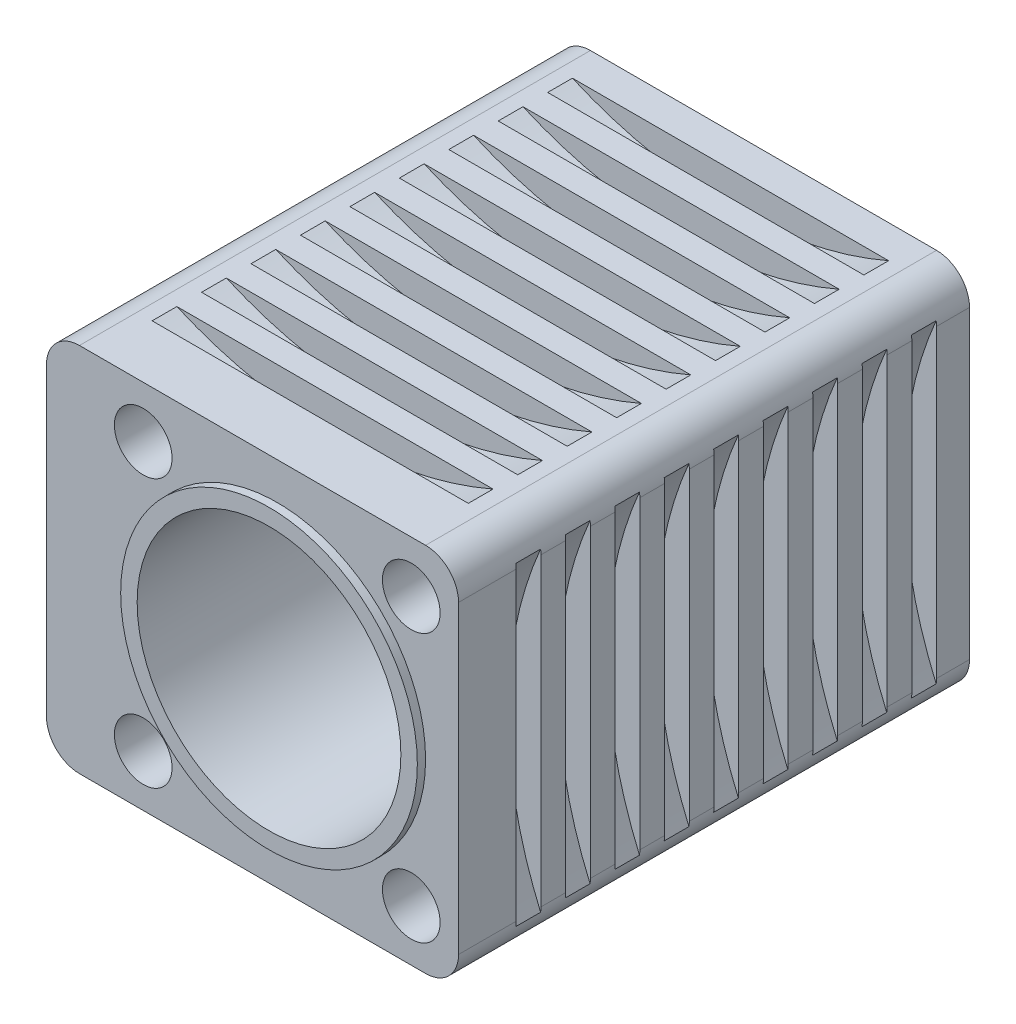
SolidWorks part; units mm, degrees
ref_plane "Front Plane" through (0, 0, 0) normal (0, 0, 1) x (1, 0, 0)
ref_plane "Top Plane" through (0, 0, 0) normal (0, 1, 0) x (1, 0, 0)
ref_plane "Right Plane" through (0, 0, 0) normal (1, 0, 0) x (0, 0, -1)
sketch "Sketch1" plane through (0, 0, 0) normal (0, 0, 1) x (1, 0, 0)
  line L1 (18, 22.5) -> (-24, 22.5)
  line L2 (22, 18.5) -> (22, -18.5)
  line L3 (18, -22.5) -> (-24, -22.5)
  line L4 (-28, 18.5) -> (-28, -18.5)
  arc A0 (22, -18.5) -> (18, -22.5) centre (18, -18.5) cw
  arc A1 (-24, -22.5) -> (-28, -18.5) centre (-24, -18.5) cw
  arc A2 (-24, 22.5) -> (-28, 18.5) centre (-24, 18.5) ccw
  arc A3 (18, 22.5) -> (22, 18.5) centre (18, 18.5) cw
  point P7 (22, -22.5)
  point P12 (-28, 22.5)
  point P15 (22, 22.5)
  dimension "D5" = 4
  dimension "D1" = 50
  dimension "D2" = 45
  dimension "D3" = 22
  dimension "D4" = 22.5
extrude "Boss-Extrude1" add sketch "Sketch1" along normal mid plane 62
sketch "Sketch2" plane through (0, 0, 31) normal (0, 0, 1) x (1, 0, 0)
  circle A0 centre (0, 0) radius 18
  dimension "D1" = 36
extrude "Boss-Extrude2" add sketch "Sketch2" along normal mid plane 2
sketch "Sketch3" plane through (0, 0, 32) normal (0, 0, 1) x (1, 0, 0)
  circle A0 centre (0, 0) radius 16
  dimension "D1" = 32
extrude "Cut-Extrude1" cut sketch "Sketch3" against normal through all
sketch "Sketch4" plane through (0, 0, -31) normal (0, 0, -1) x (-1, 0, 0)
  line L5 (28, 18.5) -> (28, -18.5) construction
  line L6 (12.8724, 2) -> (12.8724, -2)
  line L7 (23.4909, 2) -> (12.8724, 2)
  line L8 (22.61, -2) -> (12.8724, -2)
  arc A2 (23.4909, 2) -> (22.61, -2) centre (22.61, 0.097) cw
  dimension "D1" = 5.39
extrude "Cut-Extrude2" cut sketch "Sketch4" against normal blind 2
sketch "Sketch5" plane through (0, 0, -31) normal (0, 0, -1) x (-1, 0, 0)
  line L0 (0, 0) -> (-23, 0) construction
  line L1 (0, 0) -> (-16.2635, 16.2635) construction
  circle A0 centre (0, 0) radius 23 construction
  circle A1 centre (-16.2635, 16.2635) radius 3.5
  circle A2 centre (16.2635, 16.2635) radius 3.5
  circle A3 centre (16.2635, -16.2635) radius 3.5
  circle A4 centre (-16.2635, -16.2635) radius 3.5
  point P15 (0, 0)
  dimension "D1" = 46
  dimension "D3" = 7
  dimension "D2" = 45
  dimension "D4" = 4
extrude "Cut-Extrude3" cut sketch "Sketch5" against normal through all
ref_plane "Plane1" through (-3, 0, 0) normal (1, 0, 0) x (0, 0, -1)
sketch "Sketch6" plane through (-3, 0, 0) normal (1, 0, 0) x (0, 0, -1)
  line L0 (31, 18.5) -> (31, 22.5) construction
  line L1 (24, 18.5) -> (27, 18.5)
  line L2 (24, 18.5) -> (24, 66.5)
  line L3 (24, 66.5) -> (27, 66.5)
  line L4 (27, 18.5) -> (27, 66.5)
  line L5 (-31, 22.5) -> (31, 22.5) construction
  dimension "D1" = 4
  dimension "D2" = 4
  dimension "D3" = 48
  dimension "D4" = 3
revolve "Cut-Revolve1" cut sketch "Sketch6" angle 360 about L3
pattern_linear "LPattern2" count 9 spacing 6 along (0, 0, 1) of "Cut-Revolve1"
mirror "Mirror1" about plane through (0, 0, 0) normal (0, 1, 0) of "LPattern2", "Cut-Revolve1"
sketch "Sketch8" plane through (0, 0, 0) normal (0, 1, 0) x (1, 0, 0)
  line L0 (-24, 31) -> (-28, 31) construction
  line L1 (-24, 27) -> (-72, 27)
  line L2 (-24, 27) -> (-24, 24)
  line L3 (-24, 24) -> (-72, 24)
  line L4 (-72, 27) -> (-72, 24)
  line L5 (-28, -31) -> (-28, 31) construction
  dimension "D1" = 4
  dimension "D2" = 4
  dimension "D3" = 3
  dimension "D4" = 48
revolve "Cut-Revolve2" cut sketch "Sketch8" angle 360 about L4
pattern_linear "LPattern3" count 9 spacing 6 along (0, 0, 1) of "Cut-Revolve2"
mirror "Mirror2" about plane through (-3, 0, 0) normal (1, 0, 0) of "LPattern3", "Cut-Revolve2"
